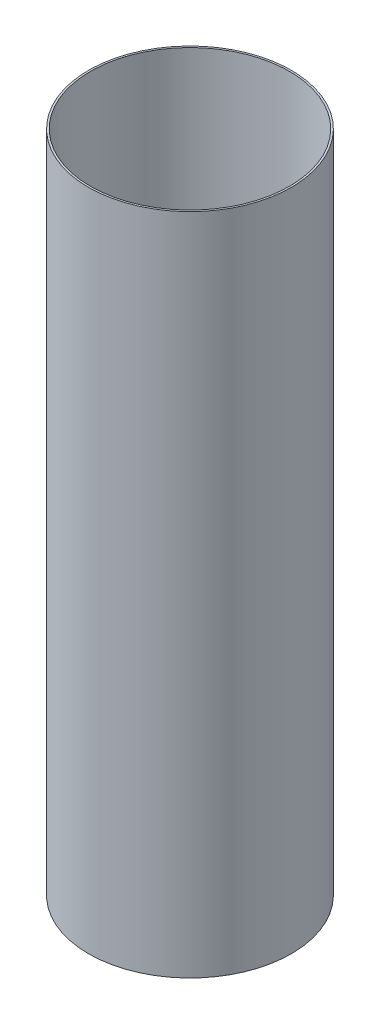
SolidWorks part; units mm, degrees
material "Thornel Mat VMA"
ref_plane "Front Plane" through (0, 0, 0) normal (0, 0, 1) x (1, 0, 0)
ref_plane "Top Plane" through (0, 0, 0) normal (0, 1, 0) x (1, 0, 0)
ref_plane "Right Plane" through (0, 0, 0) normal (1, 0, 0) x (0, 0, -1)
sketch "Sketch1" plane through (0, 0, 0) normal (0, 1, 0) x (1, 0, 0)
  circle A0 centre (0, 0) radius 77.6224
  circle A1 centre (0, 0) radius 76.2
  dimension "D1" = 155.2448
  dimension "D2" = 152.4
extrude "Boss-Extrude1" add sketch "Sketch1" along normal mid plane 508
equation "\"airframeInnerDiameter\"= 6in"
equation "\"outerDiameter\"= 6.112in"
equation "\"airframeBulkheadThickness\"= 0.125in"
equation "\"payloadAirframeLength\"= 10in"
equation "\"payloadInnerDiameter\"= 6in - 0.056in"
equation "\"payloadOuterDiameter\"= \"airframeInnerDiameter\""
equation "\"payloadLength\"= 11in"
equation "\"payloadBand\"= 2in"
equation "\"payloadOffsetFromAft\"= 6in"
equation "\"upperAirframeLength\"= 25in"
equation "\"recoveryBayInnerDiameter\"= 5.888in"
equation "\"recoveryLength\"= 8in"
equation "\"recoveryBand\"= 2in"
equation "\"recoveryCouplerOuter\"=\"airframeInnerDiameter\""
equation "\"recoveryOffsetFromAft\"= 3in"
equation "\"midAirframeLength\"= 20in"
equation "\"atsLength\"= 11in"
equation "\"atsInner\"= 5.888in"
equation "\"atsBand\"= 2in"
equation "\"atsCouplerOuter\"=\"airframeInnerDiameter\""
equation "\"atsOffsetFromAft\"= 3in"
equation "\"lowerAirframeLength\"= 40in"
equation "\"motorTubeOuterDiameter\"= 4.25in"
equation "\"motorTubeInnerDiameter\"= 4in"
equation "\"motorTubeLength\"= 32in"
equation "\"centeringRingOuterDiameter\"= \"airframeInnerDiameter\""
equation "\"centeringRingInnerDiameter\"= \"motorTubeOuterDiameter\""
equation "\"centeringRingThickness\"= 0.375in"
equation "\"topCenteringRingOffsetFromAft\"= 16.7in"
equation "\"bottomCenteringRingOffsetFromAft\"= 0.3in"
equation "\"finSlotLength\"= 8in"
equation "\"finSlotOffsetFromAft\"= 3in"
equation "\"finSlotWidth\"= 0.187in"
equation "\"motorCasingOuterDiameter\"= 3in"
equation "\"motorCasingCenteringRingThickness\"= 0.25in"
equation "\"D1@Sketch1\"=\"outerDiameter\""
equation "\"D2@Sketch1\"=\"airframeInnerDiameter\""
equation "\"D1@Boss-Extrude1\"=\"midAirframeLength\""
